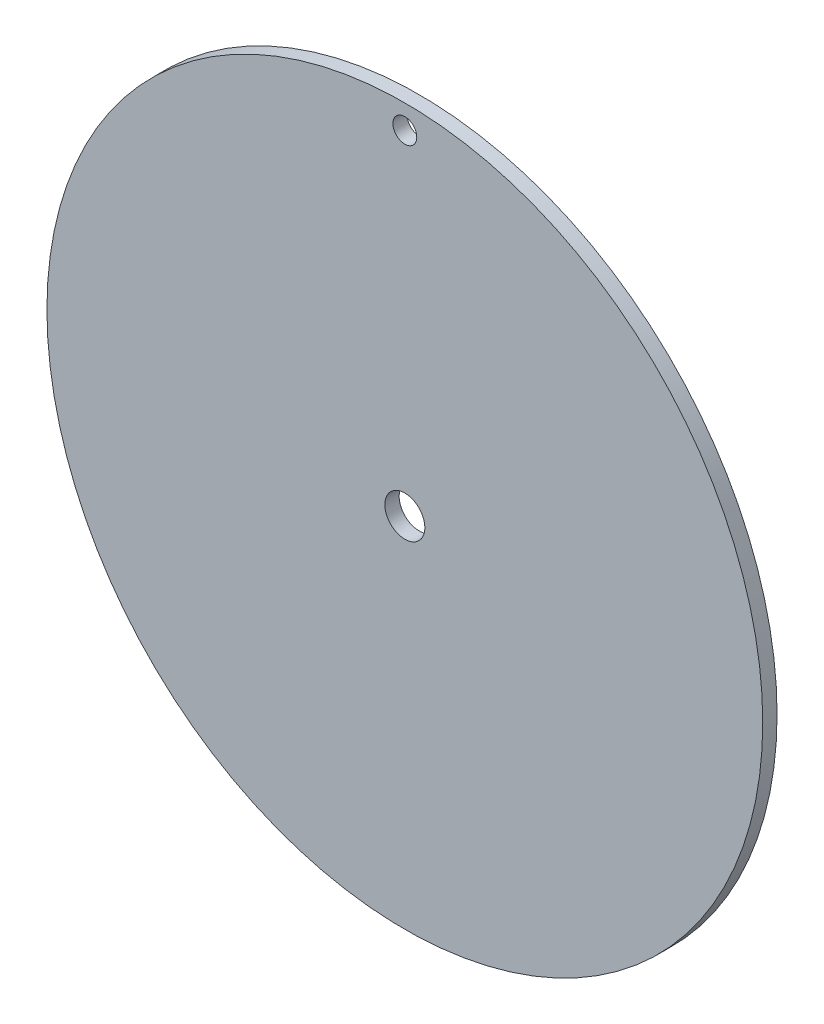
SolidWorks part; units mm, degrees
ref_plane "Front Plane" through (0, 0, 0) normal (0, 0, 1) x (1, 0, 0)
ref_plane "Top Plane" through (0, 0, 0) normal (0, 1, 0) x (1, 0, 0)
ref_plane "Right Plane" through (0, 0, 0) normal (1, 0, 0) x (0, 0, -1)
sketch "Sketch1" plane through (0, 0, 0) normal (0, 0, 1) x (1, 0, 0)
  circle A0 centre (0, 0) radius 75
  circle A1 centre (0, 70) radius 2.5
  dimension "D1" = 150
  dimension "D2" = 5
  dimension "D3" = 70
extrude "Boss-Extrude1" add sketch "Sketch1" along normal blind 3
sketch "Sketch2" plane through (0, 0, 3) normal (0, 0, 1) x (1, 0, 0)
  circle A0 centre (0, 0) radius 4.19
  dimension "D1" = 8.38
extrude "Cut-Extrude1" cut sketch "Sketch2" against normal through all
